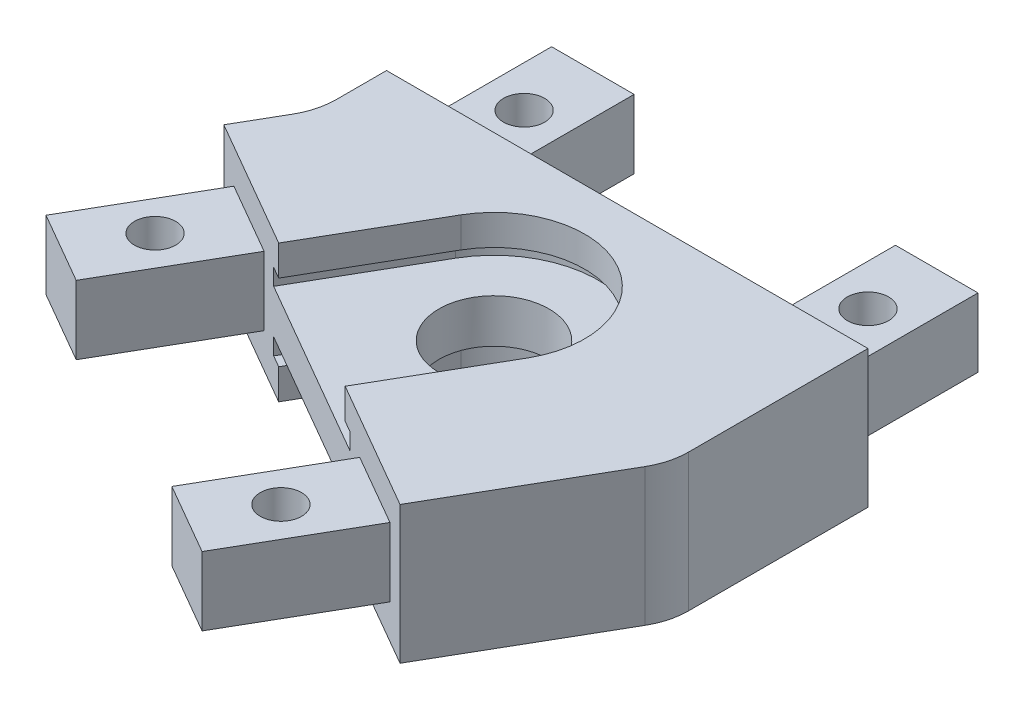
SolidWorks part; units mm, degrees
ref_plane "Front Plane" through (0, 0, 0) normal (0, 0, 1) x (1, 0, 0)
ref_plane "Top Plane" through (0, 0, 0) normal (0, 1, 0) x (1, 0, 0)
ref_plane "Right Plane" through (0, 0, 0) normal (1, 0, 0) x (0, 0, -1)
sketch "Sketch1" plane through (0, 0, 0) normal (0, 1, 0) x (1, 0, 0)
  line L0 (0, 0) -> (6, 0)
  line L1 (6, 0) -> (6, -10)
  line L2 (6, -10) -> (25, -10)
  line L3 (25, -10) -> (25, 0)
  line L4 (25, 0) -> (31, 0)
  line L5 (31, 0) -> (31, -10)
  line L7 (0, -10) -> (0, 0)
  line L8 (0, -10) -> (-2, -10)
  line L12 (33, -10) -> (31, -10)
  line L13 (3, 0) -> (3, -5) construction
  line L14 (15.5, -10) -> (15.5, 0) construction
  line L15 (-2, -10) -> (-2, -15)
  line L16 (3, -5) -> (-2, -15) construction
  line L17 (-2, -15) -> (-4.5, -19.3301)
  line L18 (-4.5, -19.3301) -> (-2.7679, -20.3301)
  line L19 (-2.7679, -20.3301) -> (-7.7679, -28.9904)
  line L20 (-7.7679, -28.9904) -> (-2.5718, -31.9904)
  line L21 (-2.5718, -31.9904) -> (2.4282, -23.3301)
  line L22 (2.4282, -23.3301) -> (18.8827, -32.8301)
  line L23 (18.8827, -32.8301) -> (13.8827, -41.4904)
  line L24 (13.8827, -41.4904) -> (19.0788, -44.4904)
  line L25 (19.0788, -44.4904) -> (24.0788, -35.8301)
  line L26 (24.0788, -35.8301) -> (25.8109, -36.8301)
  line L27 (33, -10) -> (33, -24.3782)
  line L28 (33, -24.3782) -> (25.8109, -36.8301)
  line L29 (-5.1699, -30.4904) -> (-2.6699, -26.1603) construction
  line L30 (16.4808, -42.9904) -> (18.9808, -38.6603) construction
  circle A0 centre (3, -5) radius 1.5
  circle A1 centre (28, -5) radius 1.5
  circle A2 centre (-2.6699, -26.1603) radius 1.5
  circle A3 centre (18.9808, -38.6603) radius 1.5
  dimension "D9" = 3
  dimension "D1" = 35
  dimension "D2" = 5
  dimension "D3" = 10
  dimension "D4" = 6
  dimension "D5" = 2
  dimension "D6" = 6
  dimension "D7" = 2
  dimension "D8" = 5
  dimension "D10" = 5
  dimension "D11" = 150
extrude "Boss-Extrude1" add sketch "Sketch1" along normal blind 5
sketch "Sketch2" plane through (0, 5, 0) normal (0, 1, 0) x (1, 0, 0)
  line L0 (-2, -10) -> (33, -10)
  line L1 (33, -10) -> (33, -24.3782)
  line L2 (33, -24.3782) -> (25.8109, -36.8301)
  line L3 (25.8109, -36.8301) -> (-4.5, -19.3301)
  line L4 (-4.5, -19.3301) -> (-2, -15)
  line L5 (-2, -15) -> (-2, -10)
extrude "Boss-Extrude2" add sketch "Sketch2" along normal blind 2.5
sketch "Sketch3" plane through (0, 0, 0) normal (0, -1, 0) x (1, 0, 0)
  line L6 (-2, 10) -> (33, 10)
  line L7 (33, 10) -> (33, 24.3782)
  line L8 (33, 24.3782) -> (25.8109, 36.8301)
  line L9 (25.8109, 36.8301) -> (-4.5, 19.3301)
  line L10 (-4.5, 19.3301) -> (-2, 15)
  line L11 (-2, 15) -> (-2, 10)
  line L12 (-2, 10) -> (33, 10)
  line L13 (33, 10) -> (33, 24.3782)
  line L14 (33, 24.3782) -> (25.8109, 36.8301)
  line L15 (25.8109, 36.8301) -> (-4.5, 19.3301)
  line L16 (-4.5, 19.3301) -> (-2, 15)
  line L17 (-2, 15) -> (-2, 10)
  dimension "D1" = 0
extrude "Boss-Extrude3" add sketch "Sketch3" along normal blind 2.5
sketch "Sketch4" plane through (0, 7.5, 0) normal (0, 1, 0) x (1, 0, 0)
  line L0 (-2, -15) -> (33, -24.3782) construction
sketch "Sketch5" plane through (-9.4952, 0, 16.4462) normal (-0.5, 0, 0.866) x (0.866, 0, 0.5)
  line L0 (16.6679, 7.5) -> (16.6679, 5.29)
  line L1 (5.7679, 7.5) -> (40.7679, 7.5) construction
  line L2 (16.6679, 5.29) -> (15.6679, 5.29)
  line L3 (15.6679, 5.29) -> (15.6679, 4.09)
  line L4 (15.6679, 4.09) -> (23.2679, 4.09)
  line L5 (23.2679, 4.09) -> (30.8679, 4.09)
  line L6 (30.8679, 4.09) -> (30.8679, 5.29)
  line L7 (30.8679, 5.29) -> (29.8679, 5.29)
  line L8 (29.8679, 5.29) -> (29.8679, 7.5)
  line L9 (29.8679, 7.5) -> (16.6679, 7.5)
  line L10 (13.7679, 2.5) -> (32.7679, 2.5) construction
  line L11 (13.7679, 5) -> (13.7679, 0) construction
  line L12 (32.7679, 5) -> (32.7679, 0) construction
  line L13 (23.2679, 4.09) -> (23.2679, 2.5) construction
  dimension "D1" = 13.2
  dimension "D2" = 3.41
  dimension "D3" = 1.2
  dimension "D4" = 15.2
ref_plane "Plane1" through (0, 4.09, 0) normal (0, 1, 0) x (1, 0, 0)
sketch "Sketch6" plane through (0, 4.09, 0) normal (0, 1, 0) x (1, 0, 0)
  line L0 (-2, -15) -> (33, -24.3782) construction
  circle A0 centre (15.5, -19.6891) radius 7.6
  dimension "D1" = 15.2
extrude "Cut-Extrude1" cut sketch "Sketch6" along normal blind 1.2
ref_plane "Plane2" through (0, 5.29, 0) normal (0, 1, 0) x (1, 0, 0)
sketch "Sketch8" plane through (0, 5.29, 0) normal (0, 1, 0) x (1, 0, 0)
  line L0 (-2, -15) -> (33, -24.3782) construction
  circle A0 centre (15.5, -19.6891) radius 6.6
  dimension "D1" = 13.2
extrude "Cut-Extrude2" cut sketch "Sketch8" along normal through all
ref_point "Point1"
extrude "Cut-Extrude5" cut sketch "Sketch5" against normal up to vertex and the other way through all
ref_plane "Plane3" through (0, 2.5, 0) normal (0, 1, 0) x (1, 0, 0)
mirror "Mirror1" about plane through (0, 2.5, 0) normal (0, 1, 0) of "Cut-Extrude1", "Cut-Extrude2", "Cut-Extrude5"
fillet "Fillet1" radius 5 2 edges at (33, 2.5, 24.3782) (-2, 2.5, 15)
sketch "Sketch9" plane through (0, 4.09, 0) normal (0, 1, 0) x (1, 0, 0)
  circle A0 centre (15.5, -19.6891) radius 4
  dimension "D1" = 8
extrude "Cut-Extrude6" cut sketch "Sketch9" against normal through all
